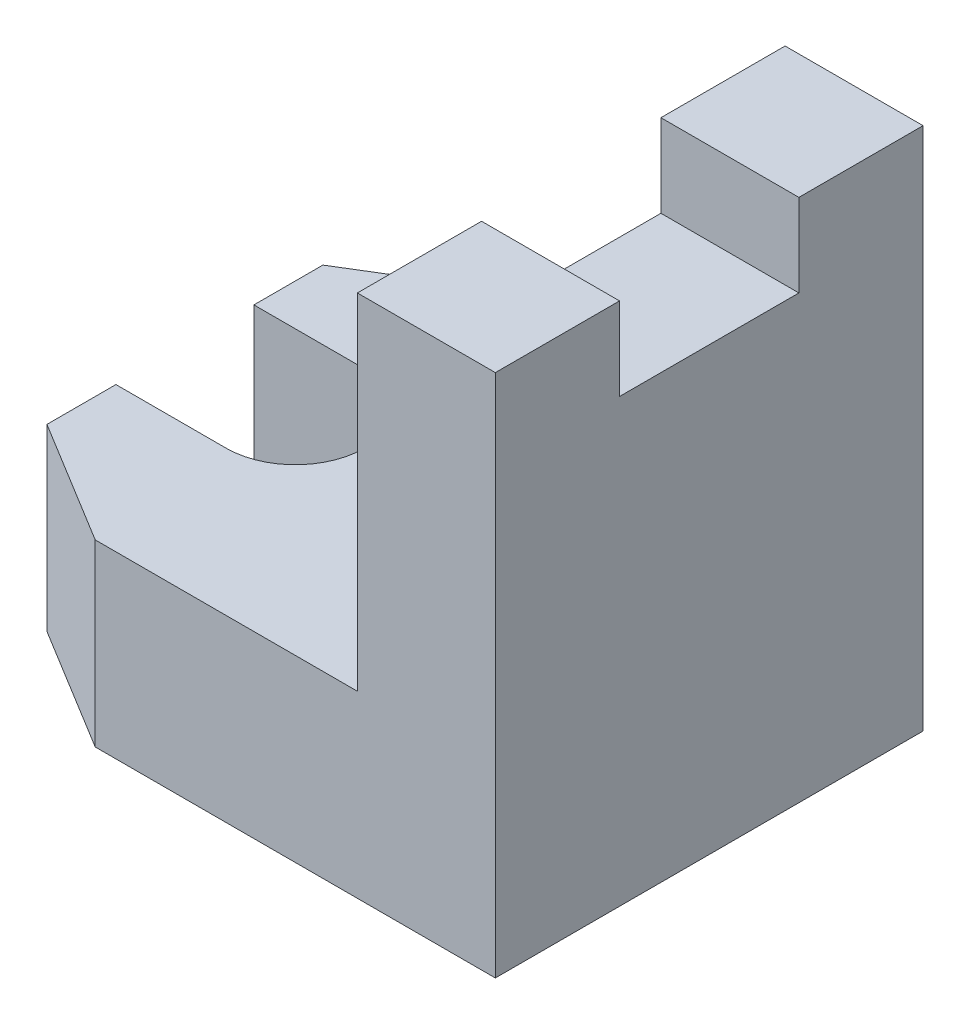
SolidWorks part; units mm, degrees
ref_plane "前视基准面" through (0, 0, 0) normal (0, 0, 1) x (1, 0, 0)
ref_plane "上视基准面" through (0, 0, 0) normal (0, 1, 0) x (1, 0, 0)
ref_plane "右视基准面" through (0, 0, 0) normal (1, 0, 0) x (0, 0, -1)
other "Configuration Table"
sketch "草图1" plane through (0, 0, 0) normal (0, 1, 0) x (1, 0, 0)
  line L0 (-180.9001, 0) -> (8864.1046, 0) construction
  line L1 (0, -180.9001) -> (0, 8864.1046) construction
  line L2 (0, 5) -> (-8, 5)
  line L3 (-8, 5) -> (-8, 10)
  line L4 (-8, 10) -> (1, 15.5)
  line L5 (1, 15.5) -> (30, 15.5)
  line L6 (30, 15.5) -> (30, -15.5)
  line L7 (1, -15.5) -> (30, -15.5)
  line L8 (-8, -10) -> (1, -15.5)
  line L9 (-8, -5) -> (-8, -10)
  line L10 (0, -5) -> (-8, -5)
  arc A0 (0, -5) -> (0, 5) centre (0, 0) ccw
  point P6 (0, 0)
  point P14 (30, 0)
  point P18 (-1.1805, 12.4089)
  point P19 (-0.9659, -12.3284)
  dimension "D1" = 5
  dimension "D2" = 20
  dimension "D3" = 8
  dimension "D4" = 29
  dimension "D5" = 38
  dimension "D6" = 31
extrude "凸台-拉伸1" add sketch "草图1" along normal blind 13
sketch "草图2" plane through (0, 13, 0) normal (0, 1, 0) x (1, 0, 0)
  line L0 (1, -15.5) -> (30, -15.5) construction
  line L1 (30, 15.5) -> (20, 15.5)
  line L2 (30, 15.5) -> (30, -15.5)
  line L3 (30, -15.5) -> (20, -15.5)
  line L4 (20, 15.5) -> (20, -15.5)
  dimension "D1" = 10
extrude "凸台-拉伸2" add sketch "草图2" along normal blind 25
sketch "草图3" plane through (0, 38, 0) normal (0, 1, 0) x (1, 0, 0)
  line L0 (-1000, 0) -> (49000, 0) construction
  line L1 (30, -15.5) -> (30, 15.5) construction
  line L2 (20, -6.5) -> (30, -6.5)
  line L3 (20, -6.5) -> (20, 6.5)
  line L4 (20, 6.5) -> (30, 6.5)
  line L5 (30, -6.5) -> (30, 6.5)
  line L6 (20, -6.5) -> (30, 6.5) construction
  line L7 (20, 6.5) -> (30, -6.5) construction
  line L8 (20, 15.5) -> (20, -15.5) construction
  point P1 (25, 0)
  dimension "D1" = 13
extrude "切除-拉伸1" cut sketch "草图3" against normal blind 6
